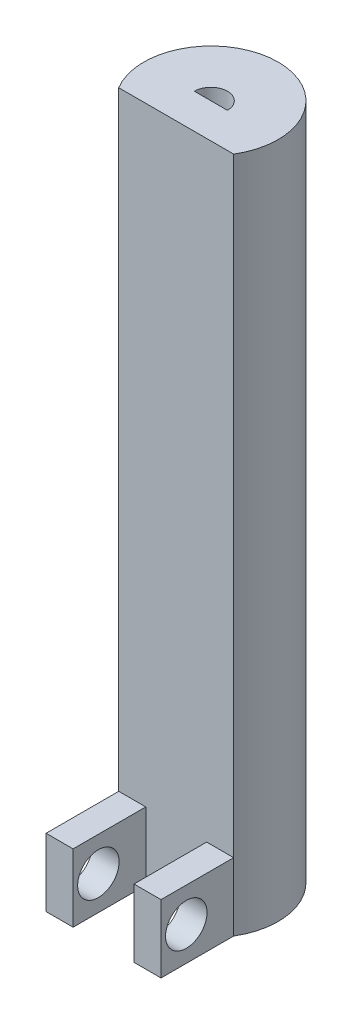
SolidWorks part; units mm, degrees
ref_plane "Front Plane" through (0, 0, 0) normal (0, 0, 1) x (1, 0, 0)
ref_plane "Top Plane" through (0, 0, 0) normal (0, 1, 0) x (1, 0, 0)
ref_plane "Right Plane" through (0, 0, 0) normal (1, 0, 0) x (0, 0, -1)
sketch "Sketch1" plane through (0, 0, 0) normal (0, 1, 0) x (1, 0, 0)
  circle A1 centre (0, 0) radius 12.6252
extrude "Boss-Extrude1" add sketch "Sketch1" against normal blind 127.254 contours A1
sketch "Sketch2" plane through (0, -127.254, 0) normal (0, -1, 0) x (-1, 0, 0)
  line L0 (-10.8004, -6.538) -> (10.8004, -6.538)
  line L1 (10.8004, -6.538) -> (10.8004, -12.6252)
  line L2 (10.8004, -12.6252) -> (-10.8004, -12.6252)
  line L3 (-10.8004, -12.6252) -> (-10.8004, -6.538)
  circle A0 centre (0, 0) radius 12.6252 construction
extrude "Cut-Extrude1" cut sketch "Sketch2" against normal blind 155.702
sketch "Sketch3" plane through (0, -127.254, 0) normal (0, -1, 0) x (-1, 0, 0)
  line L0 (3.1262, 0) -> (-3.0916, 0)
  arc A1 (-3.0916, 0) -> (3.1262, 0) centre (0.0173, 0) cw
extrude "Cut-Extrude2" cut sketch "Sketch3" against normal blind 141.0817
sketch "Sketch4" plane through (0, -127.254, 0) normal (0, -1, 0) x (1, 0, 0)
  line L0 (-10.8004, 6.538) -> (-5.7204, 6.538)
  line L1 (-10.8004, 6.538) -> (10.8004, 6.538) construction
  line L2 (-5.7204, 6.538) -> (-5.7204, 20.1914)
  line L3 (-5.7204, 20.1914) -> (-10.8004, 20.1914)
  line L4 (-10.8004, 20.1914) -> (-10.8004, 6.538)
  line L5 (10.8004, 6.538) -> (8.2919, 6.538)
  line L6 (8.2919, 6.538) -> (10.8004, 20.3961)
  line L7 (10.8004, 20.3961) -> (13.2794, 20.3961)
  line L8 (13.2794, 20.3961) -> (10.8004, 6.538)
  point P10 (0, 0)
  point P13 (-10.8004, 18.4288)
  point P14 (-8.2748, 14.243)
  point P15 (0, 0)
  point P16 (-8.1681, 17.5366)
  point P17 (-8.1765, 20.1826)
  dimension "D1" = 5.08
  dimension "D2" = 13.6535
extrude "Boss-Extrude2" add sketch "Sketch4" against normal blind 12.7552 contours L4 L0 L2 L3
sketch "Sketch15" plane through (-10.8004, 0, 0) normal (-1, 0, 0) x (0, 0, 1)
  line L0 (20.1914, -127.254) -> (6.538, -127.254) construction
  line L1 (20.1914, -114.4988) -> (20.1914, -127.254) construction
  circle A0 centre (15.4406, -120.904) radius 3.8955
  point P2 (0, 0)
  dimension "D1" = 7.791
  dimension "D2" = 6.35
  dimension "D3" = 4.7509
extrude "Cut-Extrude3" cut sketch "Sketch15" against normal up to next
mirror "Mirror2" about plane through (0, 0, 0) normal (1, 0, 0) of "Cut-Extrude3", "Boss-Extrude2"
